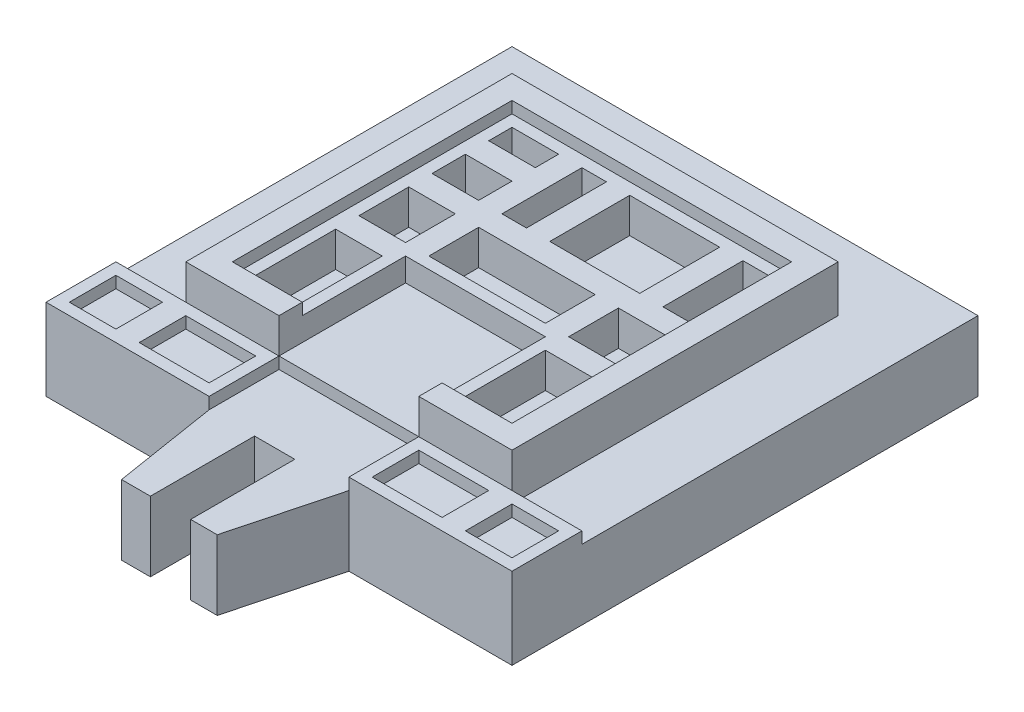
SolidWorks part; units mm, degrees
ref_plane "Alzado" through (0, 0, 0) normal (0, 0, 1) x (1, 0, 0)
ref_plane "Planta" through (0, 0, 0) normal (0, 1, 0) x (1, 0, 0)
ref_plane "Vista lateral" through (0, 0, 0) normal (1, 0, 0) x (0, 0, -1)
sketch "Croquis1" plane through (0, 0, 0) normal (0, 1, 0) x (1, 0, 0)
  line L1 (-10, -10) -> (10, -10)
  line L2 (-10, -10) -> (-10, 10)
  line L3 (-10, 10) -> (10, 10)
  line L4 (10, -10) -> (10, 10)
  line L5 (-10, -10) -> (10, 10) construction
  line L6 (-10, 10) -> (10, -10) construction
  point P0 (0, 0)
  dimension "D1" = 20
  dimension "D2" = 20
extrude "Saliente-Extruir1" add sketch "Croquis1" along normal blind 3
sketch "Croquis2" plane through (0, 3, 0) normal (0, 1, 0) x (1, 0, 0)
  line L0 (-10, 10) -> (10, 10) construction
  line L1 (-10, 10) -> (-7, 10) construction
  line L2 (-7, 10) -> (-7, 7) construction
  line L4 (7, -7) -> (-7, -7)
  line L5 (7, -7) -> (7, 7)
  line L6 (7, 7) -> (-7, 7)
  line L7 (-7, -7) -> (-7, 7)
  line L8 (7, -7) -> (-7, 7) construction
  line L9 (7, 7) -> (-7, -7) construction
  point P4 (0, 0)
  dimension "D1" = 3
  dimension "D2" = 3
extrude "Saliente-Extruir2" add sketch "Croquis2" along normal blind 2
sketch "Croquis3" plane through (0, 5, 0) normal (0, 1, 0) x (1, 0, 0)
  line L0 (-7, 7) -> (-6, 7) construction
  line L1 (7, 7) -> (-7, 7) construction
  line L2 (-6, 7) -> (-6, 6) construction
  line L4 (6, -6) -> (-6, -6)
  line L5 (6, -6) -> (6, 6)
  line L6 (6, 6) -> (-6, 6)
  line L7 (-6, -6) -> (-6, 6)
  line L8 (6, -6) -> (-6, 6) construction
  line L9 (6, 6) -> (-6, -6) construction
  point P5 (0, 0)
  dimension "D1" = 1
  dimension "D2" = 1
extrude "Cortar-Extruir1" cut sketch "Croquis3" against normal blind 2
sketch "Croquis4" plane through (0, 5, 0) normal (0, 1, 0) x (1, 0, 0)
  line L0 (-7, -7) -> (7, -7) construction
  line L3 (3, -7) -> (-3, -7)
  line L5 (0, 0) -> (-3, -7) construction
  line L6 (3, -7) -> (0, 0) construction
  line L7 (-3, -7) -> (-3, -4.3996)
  line L8 (-3, -4.3996) -> (3, -4.3996)
  line L9 (3, -4.3996) -> (3, -7)
  point P0 (0, 0)
  dimension "D1" = 6
extrude "Cortar-Extruir2" cut sketch "Croquis4" against normal blind 3
sketch "Croquis5" plane through (0, 0, 0) normal (0, 1, 0) x (1, 0, 0)
  line L0 (-3, -7) -> (-3, -10) construction
  line L1 (-10, -10) -> (10, -10) construction
  line L2 (-3, -10) -> (3, -7) construction
  line L3 (3, -7) -> (3, -10) construction
  line L4 (-3, -10) -> (-2.2879, -14.4699)
  line L5 (-2.2879, -14.4699) -> (-1.0493, -14.4699)
  line L6 (-1.0493, -14.4699) -> (-1.0493, -10)
  line L7 (-1.0493, -10) -> (0.6781, -10)
  line L8 (0.6781, -10) -> (0.6781, -14.4699)
  line L9 (0.6781, -14.4699) -> (1.8189, -14.4699)
  line L10 (1.8189, -14.4699) -> (3, -10)
  line L11 (-3, -10) -> (-1.0493, -10)
  line L12 (0.6781, -10) -> (3, -10)
  line L15 (10, -10) -> (10, 10)
  line L16 (10, 10) -> (-10, 10)
  line L17 (-10, 10) -> (-10, -10)
  line L18 (-10, -10) -> (10, -10)
  line L22 (-3, -10) -> (3, -10)
  dimension "D1" = 0
extrude "Saliente-Extruir3" add sketch "Croquis5" along normal blind 3 contours L11 L4 L5 L6 | L12 L8 L9 L10
sketch "Croquis6" plane through (0, 3, 0) normal (0, 1, 0) x (1, 0, 0)
  line L0 (-10, -10) -> (-3, -10) construction
  line L1 (-10, -10) -> (-7, -10)
  line L2 (-10, -10) -> (-10, -7)
  line L3 (-10, -7) -> (-7, -7)
  line L4 (-7, -10) -> (-7, -7)
  line L5 (-7, -7) -> (-3, -7)
  line L6 (-7, -7) -> (-7, -10)
  line L7 (-7, -10) -> (-3, -10)
  line L8 (-3, -7) -> (-3, -10)
  line L10 (10, -10) -> (7, -10)
  line L11 (10, -10) -> (10, -7)
  line L12 (10, -7) -> (7, -7)
  line L13 (7, -10) -> (7, -7)
  line L14 (7, -7) -> (3, -7)
  line L15 (7, -7) -> (7, -10)
  line L16 (7, -10) -> (3, -10)
  line L17 (3, -7) -> (3, -10)
  line L18 (-9.5, -9.5) -> (-7.5, -9.5)
  line L19 (-9.5, -9.5) -> (-9.5, -7.5)
  line L20 (-9.5, -7.5) -> (-7.5, -7.5)
  line L21 (-7.5, -9.5) -> (-7.5, -7.5)
  line L22 (-9.5, -9.5) -> (-7.5, -7.5) construction
  line L23 (-9.5, -7.5) -> (-7.5, -9.5) construction
  line L24 (-6.5, -9.5) -> (-3.5, -9.5)
  line L25 (-6.5, -9.5) -> (-6.5, -7.5)
  line L26 (-6.5, -7.5) -> (-3.5, -7.5)
  line L27 (-3.5, -9.5) -> (-3.5, -7.5)
  line L28 (-6.5, -9.5) -> (-3.5, -7.5) construction
  line L29 (-6.5, -7.5) -> (-3.5, -9.5) construction
  line L30 (3.5, -9.5) -> (6.5, -9.5)
  line L31 (3.5, -9.5) -> (3.5, -7.5)
  line L32 (3.5, -7.5) -> (6.5, -7.5)
  line L33 (6.5, -9.5) -> (6.5, -7.5)
  line L34 (3.5, -9.5) -> (6.5, -7.5) construction
  line L35 (3.5, -7.5) -> (6.5, -9.5) construction
  line L36 (7.5, -9.5) -> (9.5, -9.5)
  line L37 (7.5, -9.5) -> (7.5, -7.5)
  line L38 (7.5, -7.5) -> (9.5, -7.5)
  line L39 (9.5, -9.5) -> (9.5, -7.5)
  line L40 (7.5, -9.5) -> (9.5, -7.5) construction
  line L41 (7.5, -7.5) -> (9.5, -9.5) construction
  point P18 (-8.5, -8.5)
  point P24 (-5, -8.5)
  point P29 (5, -8.5)
  point P34 (8.5, -8.5)
  point P39 (0, 0)
  line M5 (10, -10) -> (10, 10)
  line M7 (-10, 10) -> (-10, -10)
  line M8 (-10, -10) -> (-3, -10)
  line M16 (3, -10) -> (10, -10)
  line M20 (7, -7) -> (3, -7)
  line M24 (-3, -7) -> (-7, -7)
  dimension "D1" = 0.5
  dimension "D2" = 0.5
  dimension "D3" = 0.5
  dimension "D4" = 0.5
  dimension "D5" = 0.5
  dimension "D6" = 0.5
  dimension "D7" = 0.5
  dimension "D8" = 0.5
  dimension "D9" = 0.5
  dimension "D10" = 0.5
  dimension "D11" = 0.5
  dimension "D12" = 0.5
  dimension "D13" = 0.5
  dimension "D14" = 0.5
  dimension "D15" = 0.5
  dimension "D16" = 0.5
extrude "Saliente-Extruir4" add sketch "Croquis6" along normal blind 0.5 contours L4 L3 L21 L18 L19 L20 M8 M7 | L8 L4 L27 L24 L25 L26 M24 M8 | L17 L13 L33 L30 L31 L32 M20 M16 | L13 L12 L39 L36 L37 L38 M16 M5
sketch "Croquis7" plane through (0, 3, 0) normal (0, 1, 0) x (1, 0, 0)
  line L1 (-3, -1.5681) -> (3, -1.5681)
  line L2 (-3, -1.5681) -> (-3, -4.3996)
  line L3 (-3, -4.3996) -> (3, -4.3996)
  line L4 (3, -1.5681) -> (3, -4.3996)
  line L5 (-3, -1.5681) -> (3, -4.3996) construction
  line L6 (-3, -4.3996) -> (3, -1.5681) construction
  point P0 (0, -2.9839)
extrude "Cortar-Extruir3" cut sketch "Croquis7" against normal blind 1
sketch "Croquis8" plane through (0, 3, 0) normal (0, 1, 0) x (1, 0, 0)
  line L1 (-3, -1.5681) -> (-2, -1.5681)
  line L2 (-3, -1.5681) -> (-3, -7.0086)
  line L3 (-3, -7.0086) -> (-2, -7.0086)
  line L4 (-2, -1.5681) -> (-2, -7.0086)
  line L5 (3, -1.5681) -> (2, -1.5681)
  line L6 (3, -1.5681) -> (3, -7.0086)
  line L7 (3, -7.0086) -> (2, -7.0086)
  line L8 (2, -1.5681) -> (2, -7.0086)
  dimension "D1" = 1
  dimension "D2" = 1
extrude "Saliente-Extruir5" add sketch "Croquis8" along normal blind 0.5
sketch "Croquis10" plane through (0, 3, 0) normal (0, 1, 0) x (1, 0, 0)
  line L0 (-6, -6) -> (-3, -6) construction
  line L1 (-6, 6) -> (-3, 6)
  line L2 (-6, 6) -> (-6, 4.0006)
  line L3 (-6, 4.0006) -> (-3, 4.0006)
  line L4 (-3, 6) -> (-3, 4.0006)
  line L5 (-6, 4.0006) -> (-3, 4.0006)
  line L6 (-6, 4.0006) -> (-6, 1.5681)
  line L7 (-6, 1.5681) -> (-3, 1.5681)
  line L8 (-3, 4.0006) -> (-3, 1.5681)
  line L9 (-6, 1.5681) -> (-3, 1.5681)
  line L10 (-6, 1.5681) -> (-6, -1.5681)
  line L11 (-6, -1.5681) -> (-3, -1.5681)
  line L12 (-3, 1.5681) -> (-3, -1.5681)
  line L13 (-6, -1.5681) -> (-3, -1.5681)
  line L14 (-6, -1.5681) -> (-6, -6)
  line L15 (-6, -6) -> (-3, -6)
  line L16 (-3, -1.5681) -> (-3, -6)
  line L17 (-6, -6) -> (-3, -6) construction
  line L19 (-3, 6) -> (-0.9466, 6)
  line L20 (-3, 6) -> (-3, 1.5681)
  line L21 (-3, 1.5681) -> (-0.9466, 1.5681)
  line L22 (-0.9466, 6) -> (-0.9466, 1.5681)
  line L23 (6, 6) -> (3.9121, 6)
  line L24 (6, 6) -> (6, 1.5681)
  line L25 (6, 1.5681) -> (3.9121, 1.5681)
  line L26 (3.9121, 6) -> (3.9121, 1.5681)
  line L27 (6, 1.5681) -> (3, 1.5681)
  line L28 (6, 1.5681) -> (6, -1.5681)
  line L29 (6, -1.5681) -> (3, -1.5681)
  line L30 (3, 1.5681) -> (3, -1.5681)
  line L31 (3, -1.5681) -> (6, -1.5681)
  line L32 (3, -1.5681) -> (3, -6)
  line L33 (3, -6) -> (6, -6)
  line L34 (6, -1.5681) -> (6, -6)
  line L35 (-3, 1.5681) -> (3, 1.5681)
  line L36 (-3, 1.5681) -> (-3, -1.5681)
  line L37 (-3, -1.5681) -> (3, -1.5681)
  line L38 (3, 1.5681) -> (3, -1.5681)
  line L39 (-0.9466, 6) -> (3.9121, 6)
  line L40 (-0.9466, 6) -> (-0.9466, 1.5681)
  line L41 (-0.9466, 1.5681) -> (3.9121, 1.5681)
  line L42 (3.9121, 6) -> (3.9121, 1.5681)
  line L43 (-5.5, 4.5006) -> (-3.5, 4.5006)
  line L44 (-5.5, 4.5006) -> (-5.5, 5.5)
  line L45 (-5.5, 5.5) -> (-3.5, 5.5)
  line L46 (-3.5, 4.5006) -> (-3.5, 5.5)
  line L47 (-5.5, 4.5006) -> (-3.5, 5.5) construction
  line L48 (-5.5, 5.5) -> (-3.5, 4.5006) construction
  line L49 (-5.5, 2.0681) -> (-3.5, 2.0681)
  line L50 (-5.5, 2.0681) -> (-5.5, 3.5006)
  line L51 (-5.5, 3.5006) -> (-3.5, 3.5006)
  line L52 (-3.5, 2.0681) -> (-3.5, 3.5006)
  line L53 (-5.5, 2.0681) -> (-3.5, 3.5006) construction
  line L54 (-5.5, 3.5006) -> (-3.5, 2.0681) construction
  line L55 (-5.5, -1.0681) -> (-3.5, -1.0681)
  line L56 (-5.5, -1.0681) -> (-5.5, 1.0681)
  line L57 (-5.5, 1.0681) -> (-3.5, 1.0681)
  line L58 (-3.5, -1.0681) -> (-3.5, 1.0681)
  line L59 (-5.5, -1.0681) -> (-3.5, 1.0681) construction
  line L60 (-5.5, 1.0681) -> (-3.5, -1.0681) construction
  line L61 (-5.5, -5.5) -> (-3.5, -5.5)
  line L62 (-5.5, -5.5) -> (-5.5, -2.0681)
  line L63 (-5.5, -2.0681) -> (-3.5, -2.0681)
  line L64 (-3.5, -5.5) -> (-3.5, -2.0681)
  line L65 (-5.5, -5.5) -> (-3.5, -2.0681) construction
  line L66 (-5.5, -2.0681) -> (-3.5, -5.5) construction
  line L67 (-2.5, -1.0681) -> (2.5, -1.0681)
  line L68 (-2.5, -1.0681) -> (-2.5, 1.0681)
  line L69 (-2.5, 1.0681) -> (2.5, 1.0681)
  line L70 (2.5, -1.0681) -> (2.5, 1.0681)
  line L71 (-2.5, -1.0681) -> (2.5, 1.0681) construction
  line L72 (-2.5, 1.0681) -> (2.5, -1.0681) construction
  line L73 (-2.5, 2.0681) -> (-1.4466, 2.0681)
  line L74 (-2.5, 2.0681) -> (-2.5, 5.5)
  line L75 (-2.5, 5.5) -> (-1.4466, 5.5)
  line L76 (-1.4466, 2.0681) -> (-1.4466, 5.5)
  line L77 (-2.5, 2.0681) -> (-1.4466, 5.5) construction
  line L78 (-2.5, 5.5) -> (-1.4466, 2.0681) construction
  line L79 (-0.4466, 2.0681) -> (3.4121, 2.0681)
  line L80 (-0.4466, 2.0681) -> (-0.4466, 5.5)
  line L81 (-0.4466, 5.5) -> (3.4121, 5.5)
  line L82 (3.4121, 2.0681) -> (3.4121, 5.5)
  line L83 (-0.4466, 2.0681) -> (3.4121, 5.5) construction
  line L84 (-0.4466, 5.5) -> (3.4121, 2.0681) construction
  line L85 (4.4121, 2.0681) -> (5.5, 2.0681)
  line L86 (4.4121, 2.0681) -> (4.4121, 5.5)
  line L87 (4.4121, 5.5) -> (5.5, 5.5)
  line L88 (5.5, 2.0681) -> (5.5, 5.5)
  line L89 (4.4121, 2.0681) -> (5.5, 5.5) construction
  line L90 (4.4121, 5.5) -> (5.5, 2.0681) construction
  line L91 (3.5, -1.0681) -> (5.5, -1.0681)
  line L92 (3.5, -1.0681) -> (3.5, 1.0681)
  line L93 (3.5, 1.0681) -> (5.5, 1.0681)
  line L94 (5.5, -1.0681) -> (5.5, 1.0681)
  line L95 (3.5, -1.0681) -> (5.5, 1.0681) construction
  line L96 (3.5, 1.0681) -> (5.5, -1.0681) construction
  line L97 (3.5, -5.5) -> (5.5, -5.5)
  line L98 (3.5, -5.5) -> (3.5, -2.0681)
  line L99 (3.5, -2.0681) -> (5.5, -2.0681)
  line L100 (5.5, -5.5) -> (5.5, -2.0681)
  line L101 (3.5, -5.5) -> (5.5, -2.0681) construction
  line L102 (3.5, -2.0681) -> (5.5, -5.5) construction
  point P29 (-4.5, 5.0003)
  point P35 (-4.5, 2.7844)
  point P40 (-4.5, 0)
  point P45 (-4.5, -3.7841)
  point P50 (0, 0)
  point P56 (-1.9733, 3.7841)
  point P61 (1.4828, 3.7841)
  point P66 (4.9561, 3.7841)
  point P71 (4.5, 0)
  point P76 (4.5, -3.7841)
  line M1 (-3, -1.5681) -> (3, -1.5681)
  line M2 (3, -1.5681) -> (3, -6)
  line M3 (3, -6) -> (6, -6)
  line M4 (6, -6) -> (6, 6)
  line M5 (6, 6) -> (-6, 6)
  line M6 (-6, 6) -> (-6, -6)
  line M7 (-6, -6) -> (-3, -6)
  line M8 (-3, -6) -> (-3, -1.5681)
  dimension "D1" = 0.5
  dimension "D2" = 0.5
  dimension "D3" = 0.5
  dimension "D4" = 0.5
  dimension "D5" = 0.5
  dimension "D6" = 0.5
  dimension "D7" = 0.5
  dimension "D8" = 0.5
  dimension "D9" = 0.5
  dimension "D10" = 0.5
  dimension "D11" = 0.5
  dimension "D12" = 0.5
  dimension "D13" = 0.5
  dimension "D14" = 0.5
  dimension "D15" = 0.5
  dimension "D16" = 0.5
  dimension "D17" = 0.5
  dimension "D18" = 0.5
  dimension "D19" = 0.5
  dimension "D20" = 0.5
  dimension "D21" = 0.5
  dimension "D22" = 0.5
  dimension "D23" = 0.5
  dimension "D24" = 0.5
  dimension "D25" = 0.5
  dimension "D26" = 0.5
  dimension "D27" = 0.5
  dimension "D28" = 0.5
  dimension "D29" = 0.5
  dimension "D30" = 0.5
  dimension "D31" = 0.5
  dimension "D32" = 0.5
  dimension "D33" = 0.5
  dimension "D34" = 0.5
  dimension "D35" = 0.5
  dimension "D36" = 0.5
  dimension "D37" = 0.5
  dimension "D38" = 0.5
  dimension "D39" = 0.5
extrude "Saliente-Extruir6" add sketch "Croquis10" along normal blind 1.5 contours L11 L64 L61 L62 L63 M6 M7 M8 | L12 L7 L11 L58 L55 L56 L57 M6 | L8 L3 L7 L52 L49 L50 L51 M6 | L22 L4 L8 L21 L76 L73 L74 L75 M5 | L22 L35 L27 L26 L82 L79 L80 L81 M5 | L35 L21 L12 L30 L70 L67 L68 L69 M1 | L26 L25 L88 L85 L86 L87 M5 M4 | L27 L30 L29 L25 L94 L91 L92 L93 M4 | L29 L100 L97 L98 L99 M4 M2 M3 | L4 L3 L46 L43 L44 L45 M5 M6
sketch "Croquis11" plane through (0, 2, 0) normal (0, 1, 0) x (1, 0, 0)
  line L4 (-3, -1.5681) -> (-3, -7)
  line L5 (-3, -7) -> (3, -7)
  line L6 (3, -7) -> (3, -1.5681)
  line L7 (3, -1.5681) -> (-3, -1.5681)
  line L8 (-3, -1.5681) -> (-3, -7)
  line L9 (-3, -7) -> (3, -7)
  line L10 (3, -7) -> (3, -1.5681)
  line L11 (3, -1.5681) -> (-3, -1.5681)
  dimension "D1" = 0
extrude "Saliente-Extruir7" add sketch "Croquis11" along normal blind 1.5
sketch "Croquis12" plane through (0, 0, 0) normal (0, -1, 0) x (1, 0, 0)
  circle A0 centre (0, 0) radius 1.575
  dimension "D1" = 3.15
extrude "Cortar-Extruir4" cut sketch "Croquis12" against normal blind 2.5
